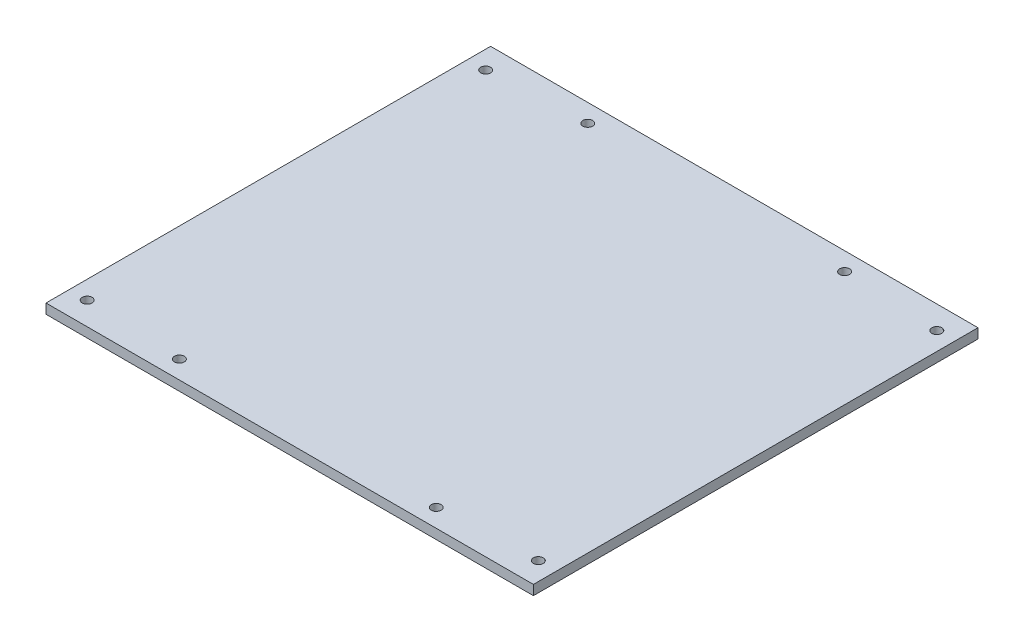
SolidWorks part; units mm, degrees
ref_plane "Front Plane" through (0, 0, 0) normal (0, 0, 1) x (1, 0, 0)
ref_plane "Top Plane" through (0, 0, 0) normal (0, 1, 0) x (1, 0, 0)
ref_plane "Right Plane" through (0, 0, 0) normal (1, 0, 0) x (0, 0, -1)
sketch "Sketch1" plane through (0, 0, 0) normal (0, 1, 0) x (1, 0, 0)
  line L0 (0, 73.106) -> (0, -66.7284) construction
  line L1 (25, -25) -> (-25, -25) construction
  line L2 (25, -25) -> (25, 25) construction
  line L3 (25, 25) -> (-25, 25) construction
  line L4 (-25, -25) -> (-25, 25) construction
  line L5 (-74, 40) -> (-55, 40) construction
  line L6 (-74, 40) -> (-74, -23) construction
  line L7 (-74, -23) -> (-55, -23) construction
  line L8 (-55, 40) -> (-55, -23) construction
  line L9 (55, 40) -> (55, -23) construction
  line L10 (74, -23) -> (55, -23) construction
  line L11 (74, 40) -> (74, -23) construction
  line L12 (74, 40) -> (55, 40) construction
  line L14 (-74, 60) -> (74, 60)
  line L15 (-74, 60) -> (-74, -75)
  line L16 (-74, -75) -> (74, -75)
  line L17 (74, 60) -> (74, -75)
  point P4 (25, 0)
  point P6 (0, 25)
  dimension "D1" = 50
  dimension "D2" = 50
  dimension "D3" = 63
  dimension "D4" = 19
  dimension "D5" = 30
  dimension "D6" = 40
  dimension "D7" = 60
  dimension "D8" = 75
  dimension "D9" = 148
  dimension "D10" = 20
extrude "Boss-Extrude1" add sketch "Sketch1" along normal blind 2.9718
sketch "Sketch2" plane through (0, 2.9718, 0) normal (0, 1, 0) x (1, 0, 0)
  line L0 (74, 60) -> (-74, 60) construction
  line L1 (-74, 60) -> (-74, -75) construction
  line L2 (-68.5, -68) -> (-68.5, -75) construction
  line L3 (-74, -75) -> (74, -75) construction
  line L4 (-68.5, 60) -> (-68.5, 53) construction
  line L5 (0, 0) -> (0, 85.1273) construction
  line L6 (-39, 54.5) -> (39, 54.5) construction
  circle A0 centre (-68.5, 53) radius 1.5
  circle A1 centre (-68.5, -68) radius 1.5
  circle A2 centre (68.5, -68) radius 1.5
  circle A3 centre (68.5, 53) radius 1.5
  circle A4 centre (-39, 54.5) radius 1.5
  circle A5 centre (39, 54.5) radius 1.5
  circle A6 centre (-39, -69.5) radius 1.5
  circle A7 centre (39, -69.5) radius 1.5
  point P27 (0, 54.5)
  point P28 (0, 0)
  dimension "D1" = 3
  dimension "D6" = 3
  dimension "D2" = 7
  dimension "D3" = 5.5
  dimension "D4" = 35
  dimension "D5" = 5.5
  dimension "D7" = 5.5
extrude "Cut-Extrude1" cut sketch "Sketch2" against normal through all
